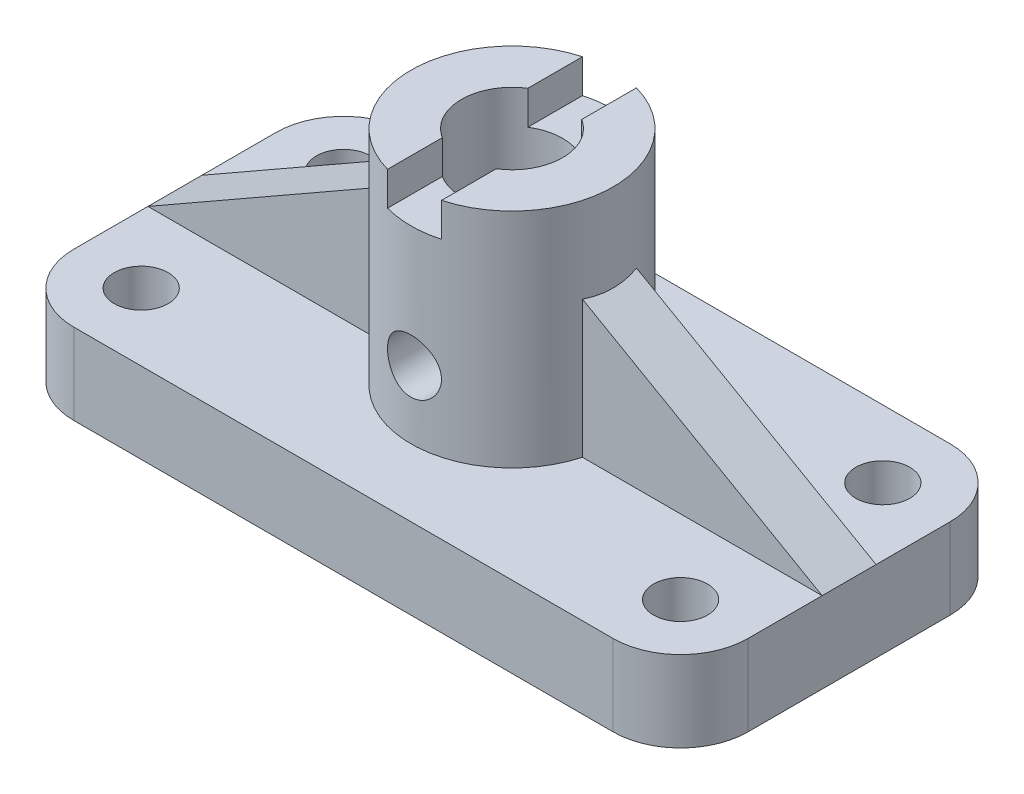
SolidWorks part; units mm, degrees
ref_plane "前视基准面" through (0, 0, 0) normal (0, 0, 1) x (1, 0, 0)
ref_plane "上视基准面" through (0, 0, 0) normal (0, 1, 0) x (1, 0, 0)
ref_plane "右视基准面" through (0, 0, 0) normal (1, 0, 0) x (0, 0, -1)
other "Configuration Table"
sketch "草图1" plane through (0, 0, 0) normal (0, 1, 0) x (1, 0, 0)
  line L5 (-40, -25) -> (40, -25)
  line L6 (-50, -15) -> (-50, 15)
  line L7 (-40, 25) -> (40, 25)
  line L8 (50, -15) -> (50, 15)
  line L9 (-50, -25) -> (50, 25) construction
  line L10 (-50, 25) -> (50, -25) construction
  arc A0 (40, -25) -> (50, -15) centre (40, -15) ccw
  arc A1 (-50, 15) -> (-40, 25) centre (-40, 15) cw
  arc A2 (-40, -25) -> (-50, -15) centre (-40, -15) cw
  arc A3 (40, 25) -> (50, 15) centre (40, 15) cw
  circle A4 centre (-40, 15) radius 4
  circle A5 centre (-40, -15) radius 4
  circle A6 centre (40, 15) radius 4
  circle A8 centre (40, -15) radius 4
  point P0 (0, 0)
  dimension "D3" = 10
  dimension "D4" = 8
  dimension "D1" = 100
  dimension "D2" = 50
extrude "凸台-拉伸2" add sketch "草图1" along normal blind 12
sketch "草图4" plane through (0, 12, 0) normal (0, 1, 0) x (1, 0, 0)
  circle A1 centre (0, 0) radius 15
  circle A2 centre (0, 0) radius 7.5
  dimension "D1" = 30
  dimension "D2" = 15
extrude "凸台-拉伸3" add sketch "草图4" along normal blind 33
ref_plane "基准面1" through (0, 0, 25) normal (0, 0, 1) x (1, 0, 0)
sketch "草图5" plane through (0, 0, 25) normal (0, 0, 1) x (1, 0, 0)
  line L0 (0, 12) -> (0, 22) construction
  line L1 (-40, 12) -> (40, 12) construction
  circle A0 centre (0, 22) radius 4
  dimension "D2" = 8
  dimension "D1" = 10
extrude "切除-拉伸12" cut sketch "草图5" against normal through all both and the other way through all
sketch "草图10" plane through (0, 0, 0) normal (0, 0, 1) x (1, 0, 0)
  line L0 (-50, 12) -> (-15, 32)
  line L1 (-15, 45) -> (-15, 12) construction
  dimension "D1" = 20
rib "筋9" sketch "草图10" sketch "草图10" thickness 8 extrusion direction parallel to sketch draft on no parameters "D1"=8
sketch "草图13" plane through (0, 0, 25) normal (0, 0, 1) x (1, 0, 0)
  line L2 (7.5, 45) -> (-7.5, 45) construction
  line L4 (0, 40) -> (4, 40)
  line L5 (0, 40) -> (-4, 40)
  line L6 (4, 40) -> (4, 45)
  line L7 (4, 45) -> (0, 45)
  line L8 (0, 45) -> (-4, 45)
  line L9 (-4, 45) -> (-4, 40)
  dimension "D1" = 5
  dimension "D2" = 4
extrude "切除-拉伸14" cut sketch "草图13" against normal through all both and the other way through all
sketch "草图14" plane through (0, 0, 0) normal (0, 1, 0) x (1, 0, 0)
  circle A0 centre (0, 0) radius 7.5
extrude "切除-拉伸15" cut sketch "草图14" along normal through all both and the other way through all
mirror "镜向1" about plane through (0, 0, 0) normal (1, 0, 0) of "筋9"
